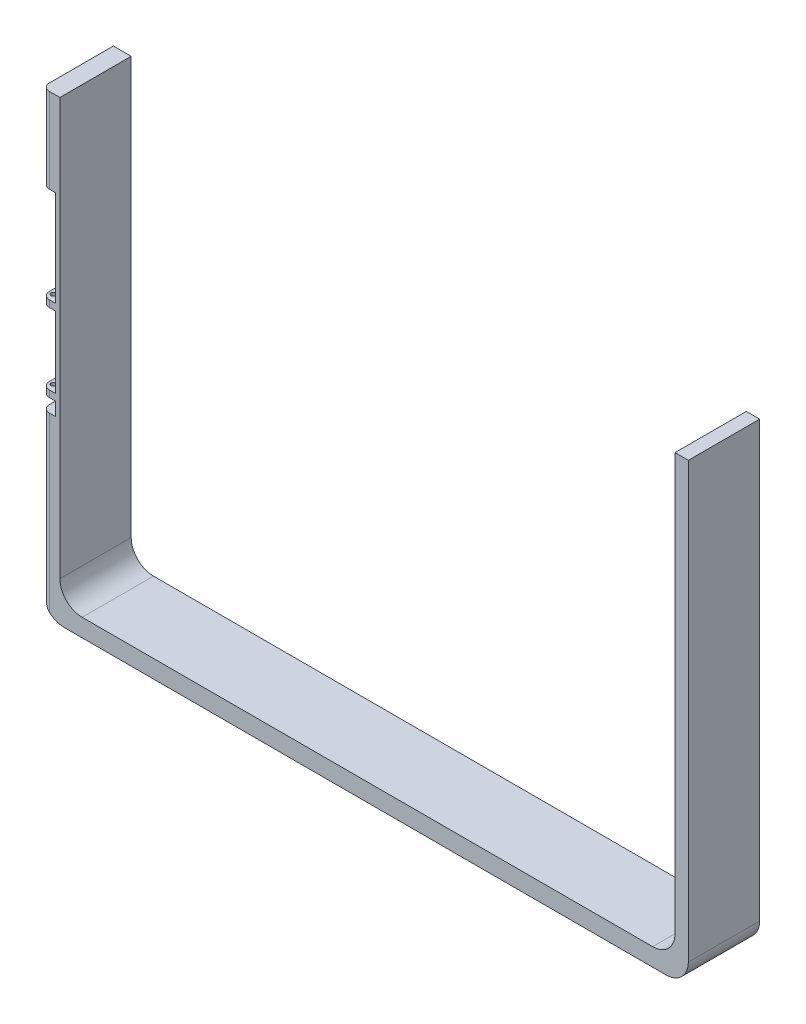
SolidWorks part; units mm, degrees
ref_plane "前视基准面" through (0, 0, 0) normal (0, 0, 1) x (1, 0, 0)
ref_plane "上视基准面" through (0, 0, 0) normal (0, 1, 0) x (1, 0, 0)
ref_plane "右视基准面" through (0, 0, 0) normal (1, 0, 0) x (0, 0, -1)
sketch "草图1" plane through (0, 0, 0) normal (0, 0, 1) x (1, 0, 0)
  line L0 (194.7879, 116.3636) -> (200.7879, 116.3636)
  line L1 (-89.2121, 116.3636) -> (-81.2121, 116.3636)
  line L2 (-89.2121, 116.3636) -> (-89.2121, -78.6364)
  line L3 (-79.2121, -88.6364) -> (190.7879, -88.6364)
  line L4 (200.7879, 116.3636) -> (200.7879, -78.6364)
  line L6 (-81.2121, 116.3636) -> (-81.2121, -70.6364)
  line L7 (-71.2121, -80.6364) -> (184.7879, -80.6364)
  line L8 (194.7879, 116.3636) -> (194.7879, -70.6364)
  arc A0 (-81.2121, -70.6364) -> (-71.2121, -80.6364) centre (-71.2121, -70.6364) ccw
  arc A1 (184.7879, -80.6364) -> (194.7879, -70.6364) centre (184.7879, -70.6364) ccw
  arc A2 (190.7879, -88.6364) -> (200.7879, -78.6364) centre (190.7879, -78.6364) ccw
  arc A3 (-89.2121, -78.6364) -> (-79.2121, -88.6364) centre (-79.2121, -78.6364) ccw
  point P14 (200.7879, -88.6364)
  point P17 (-89.2121, -88.6364)
  dimension "D6" = 10
  dimension "D1" = 290
  dimension "D2" = 205
  dimension "D3" = 8
  dimension "D4" = 6
  dimension "D5" = 8
extrude "凸台-拉伸1" add sketch "草图1" along normal blind 32
sketch "草图2" plane through (0, 0, 0) normal (0, 0, -1) x (-1, 0, 0)
  line L0 (79.2121, -88.6364) -> (-190.7879, -88.6364) construction
  line L1 (-200.7879, -78.6364) -> (-200.7879, 116.3636) construction
  circle A0 centre (-182.7879, -84.6364) radius 2.1
  circle A1 centre (-55.7879, -84.6364) radius 2.1
  circle A2 centre (71.2121, -84.6364) radius 2.1
  dimension "D1" = 4.2
  dimension "D2" = 4
  dimension "D3" = 18
  dimension "D4" = 3
extrude "切除-拉伸1" cut sketch "草图2" against normal blind 5
sketch "草图3" plane through (-89.2121, 0, 0) normal (-1, 0, 0) x (0, 0, 1)
  line L0 (32, 116.3636) -> (32, -78.6364) construction
  line L1 (32, -8.6364) -> (26, -8.6364)
  line L2 (32, -8.6364) -> (32, -2.6364)
  line L3 (32, -2.6364) -> (26, -2.6364)
  line L4 (26, -8.6364) -> (26, -2.6364)
  line L5 (32, -88.6364) -> (0, -88.6364) construction
  line L6 (32, 0.3636) -> (26, 0.3636)
  line L7 (32, 0.3636) -> (32, 32.3636)
  line L8 (32, 32.3636) -> (26, 32.3636)
  line L9 (26, 0.3636) -> (26, 32.3636)
  line L10 (32, 35.3636) -> (26, 35.3636)
  line L11 (32, 35.3636) -> (32, 78.3636)
  line L12 (32, 78.3636) -> (26, 78.3636)
  line L13 (26, 35.3636) -> (26, 78.3636)
  dimension "D1" = 80
  dimension "D2" = 6
  dimension "D3" = 6
  dimension "D4" = 3
  dimension "D5" = 32
  dimension "D6" = 6
  dimension "D7" = 3
  dimension "D8" = 6
  dimension "D9" = 43
extrude "切除-拉伸2" cut sketch "草图3" against normal blind 6
sketch "草图4" plane through (0, 35.3636, 0) normal (0, 1, 0) x (1, 0, 0)
  line L0 (-83.2121, -32) -> (-89.2121, -32) construction
  line L1 (-89.2121, -26) -> (-89.2121, -32) construction
  circle A0 centre (-87.2121, -29) radius 1
  dimension "D3" = 2
  dimension "D1" = 3
  dimension "D2" = 2
extrude "切除-拉伸3" cut sketch "草图4" against normal blind 38
sketch "草图6" plane through (0, -88.6364, 0) normal (0, -1, 0) x (1, 0, 0)
  line L0 (-89.2121, 32) -> (-85.9121, 32)
  line L1 (-79.2121, 32) -> (-89.2121, 32) construction
  line L3 (-89.2121, 32) -> (-89.2121, 0) construction
  line L4 (-89.2121, 28.7) -> (-89.2121, 32)
  arc A0 (-85.9121, 32) -> (-89.2121, 28.7) centre (-85.9121, 28.7) ccw
  dimension "D1" = 3.3
  dimension "D2" = 3.3
extrude "切除-拉伸4" cut sketch "草图6" against normal through all
